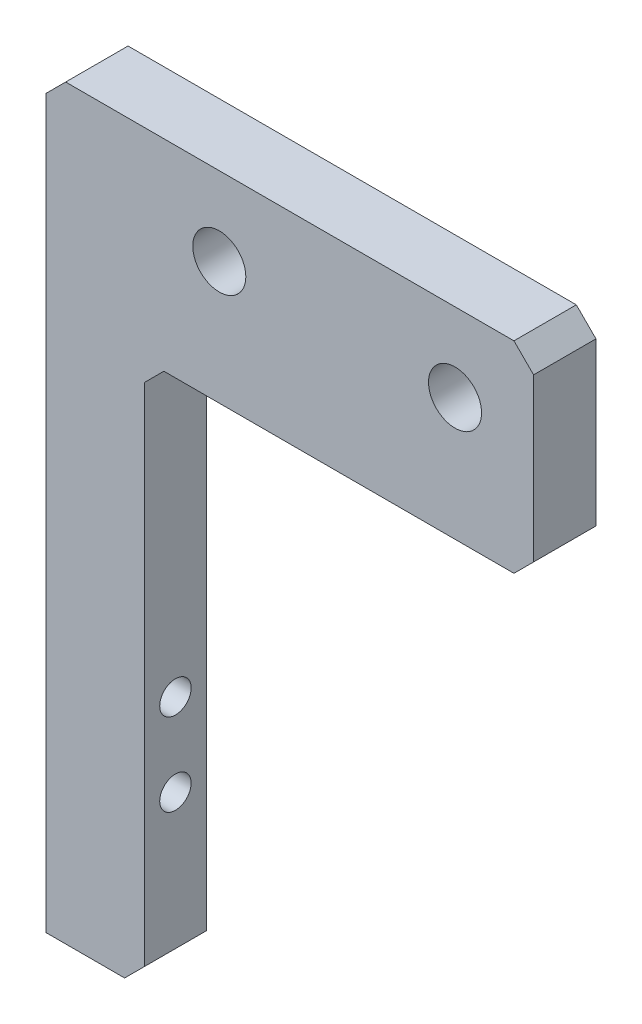
SolidWorks part; units mm, degrees
ref_plane "Front Plane" through (0, 0, 0) normal (0, 0, 1) x (1, 0, 0)
ref_plane "Top Plane" through (0, 0, 0) normal (0, 1, 0) x (1, 0, 0)
ref_plane "Right Plane" through (0, 0, 0) normal (1, 0, 0) x (0, 0, -1)
sketch "Sketch1" plane through (0, 0, 0) normal (0, 0, 1) x (1, 0, 0)
  line L0 (-6, 0) -> (6, 0)
  line L1 (-17, 10.289) -> (-17, -6.25)
  line L2 (-17, -6.25) -> (4.3359, -6.25)
  line L3 (-14.82, -6.25) -> (-14.82, -34)
  line L4 (-14.82, -24) -> (17.405, -24)
  point P4 (0, 0)
  dimension "D1" = 12
  dimension "D2" = 11
  dimension "D3" = 6.25
  dimension "D4" = 2.18
  dimension "D5" = 27.75
  dimension "D6" = 10
sketch "Sketch2" plane through (0, 0, 0) normal (0, 0, 1) x (1, 0, 0)
  line L0 (-9.82, -6.25) -> (10, -6.25)
  line L1 (-17, -6.25) -> (4.3359, -6.25) construction
  line L2 (10, -6.25) -> (10, 4)
  line L3 (10, 4) -> (-14.82, 4)
  line L4 (-14.82, 4) -> (-14.82, -34)
  line L5 (-14.82, -34) -> (-9.82, -34)
  line L6 (-9.82, -34) -> (-9.82, -6.25)
  line L7 (-6, 0) -> (6, 0) construction
  dimension "D1" = 5
  dimension "D2" = 4
  dimension "D3" = 4
extrude "Boss-Extrude1" add sketch "Sketch2" along normal blind 3.175
hole_wizard "M2.5 Clearance Hole1" positions "Sketch3" profile "Sketch4" hole size "M2.5" standard "ANSI Metric" end condition through all
sketch "Sketch3" plane through (0, 0, 3.175) normal (0, 0, 1) x (1, 0, 0)
  point P0 (-6, 0)
  point P3 (6, 0)
sketch "Sketch4" plane through (-6, 0, 3.175) normal (1, 0, 0) x (0, -1, 0)
  line L0 (0, 0) -> (0, 3.175)
  line L1 (0, 3.175) -> (1.35, 3.175)
  line L2 (1.35, 3.175) -> (1.35, 0)
  line L5 (1.35, 0) -> (0, 0)
  line L11 (0, -6.35) -> (0, 107.95) construction
  dimension "Thru Hole Dia." = 2.7
  dimension "Thru Hole Depth" = 3.175
chamfer "Chamfer1" distance 1 angle 45 5 edges at (-9.82, -6.25, 1.5875) (-14.82, 4, 1.5875) (10, 4, 1.5875) (10, -6.25, 1.5875) (-9.82, -34, 1.5875)
hole_wizard "Tap Drill for M2x0.4 Tap1" positions "Sketch5" profile "Sketch6" hole size "M2x0.4" standard "ANSI Metric" end condition through all
sketch "Sketch5" plane through (-14.82, 0, 0) normal (-1, 0, 0) x (0, 0, 1)
  line L0 (1.5875, -34) -> (1.5875, -21.9) construction
  line L1 (3.175, -34) -> (0, -34) construction
  line L3 (1.5875, -24) -> (0, -24) construction
  line L4 (0, -6.25) -> (0, -34) construction
  point P0 (1.5875, -21.9)
  point P19 (1.5875, -26.1)
  dimension "D1" = 2.1
sketch "Sketch6" plane through (-14.82, -21.9, 1.5875) normal (0, 1, 0) x (0, 0, 1)
  line L0 (0, 0) -> (0, 24.82)
  line L1 (0, 24.82) -> (0.8, 24.82)
  line L2 (0.8, 24.82) -> (0.8, 0)
  line L5 (0.8, 0) -> (0, 0)
  line L11 (0, -6.35) -> (0, 107.95) construction
  dimension "Thru Hole Dia." = 1.6
  dimension "Thru Hole Depth" = 24.82
